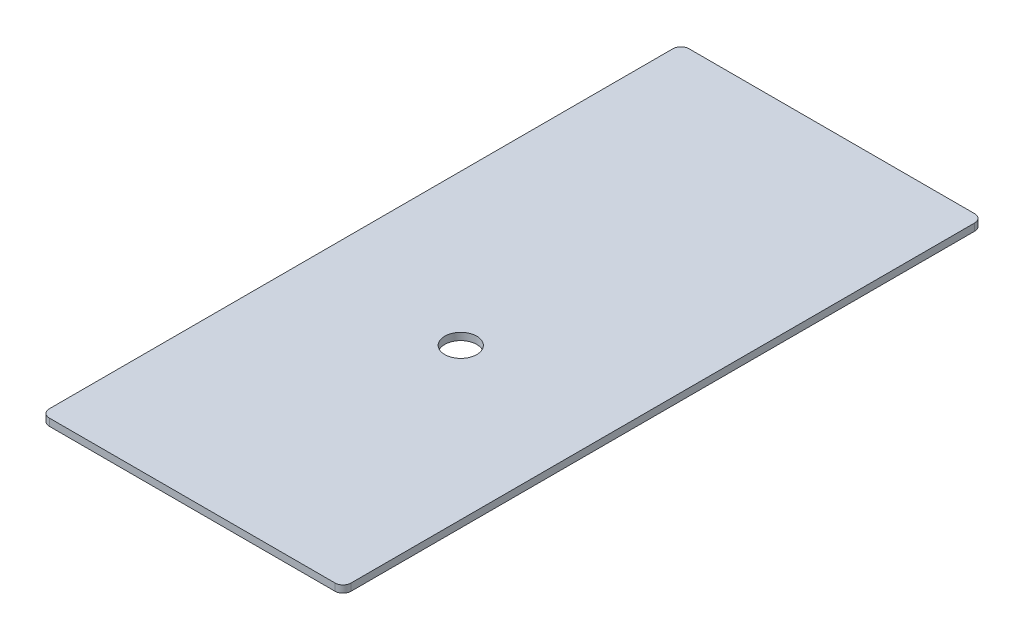
SolidWorks part; units mm, degrees
material "Acrylic (Medium-high impact)"
ref_plane "Front Plane" through (0, 0, 0) normal (0, 0, 1) x (1, 0, 0)
ref_plane "Top Plane" through (0, 0, 0) normal (0, 1, 0) x (1, 0, 0)
ref_plane "Right Plane" through (0, 0, 0) normal (1, 0, 0) x (0, 0, -1)
sketch "Sketch1" plane through (0, 0, 0) normal (0, 1, 0) x (1, 0, 0)
  line L1 (0, 0) -> (188.7, 0)
  line L2 (0, 0) -> (0, 400)
  line L3 (0, 400) -> (188.7, 400)
  line L4 (188.7, 0) -> (188.7, 400)
  dimension "D1" = 188.7
  dimension "D2" = 400
extrude "Boss-Extrude1" add sketch "Sketch1" along normal blind 4.5
fillet "Fillet1" radius 5 4 edges at (0, 2.25, -400) (188.7, 2.25, -400) (0, 2.25, 0) (188.7, 2.25, 0)
sketch "Sketch3" plane through (0, 4.5, 0) normal (0, 1, 0) x (1, 0, 0)
  circle A4 centre (94.3066, 168) radius 10
  point P2 (0, 0)
extrude "Cut-Extrude2" cut sketch "Sketch3" against normal blind 20
